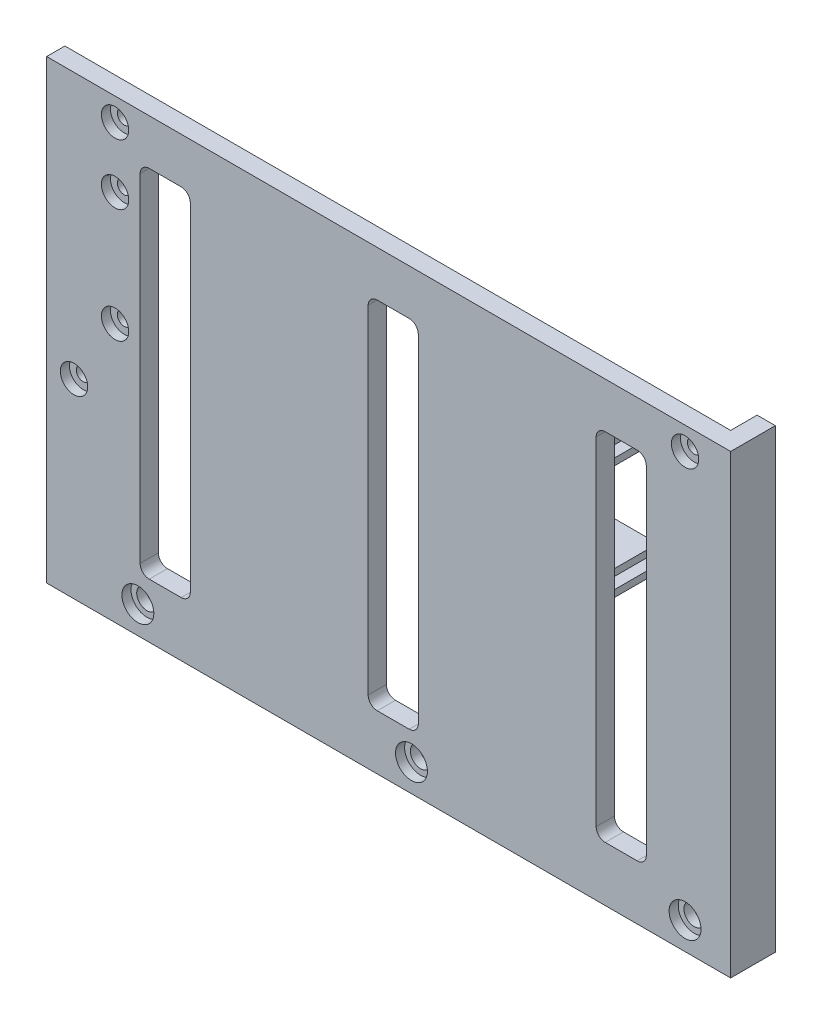
SolidWorks part; units mm, degrees
ref_plane "Front Plane" through (0, 0, 0) normal (0, 0, 1) x (1, 0, 0)
ref_plane "Top Plane" through (0, 0, 0) normal (0, 1, 0) x (1, 0, 0)
ref_plane "Right Plane" through (0, 0, 0) normal (1, 0, 0) x (0, 0, -1)
sketch "Sketch1" plane through (0, 0, 0) normal (0, 1, 0) x (1, 0, 0)
  line L1 (-75, -60) -> (75, -60)
  line L2 (-75, -60) -> (-75, -56)
  line L3 (-75, -56) -> (75, -56)
  line L4 (75, -60) -> (75, -56)
  dimension "D1" = 4
extrude "Boss-Extrude1" add sketch "Sketch1" along normal blind 100 contours L1 L4 L3 L2
sketch "Sketch7" plane through (0, 0, 60) normal (0, 0, 1) x (1, 0, 0)
  line L1 (-7.8417, 2) -> (47.18, 2)
  line L2 (-7.8417, 2) -> (-7.8417, 11.6942)
  line L3 (-7.8417, 11.6942) -> (47.18, 11.6942)
  line L4 (47.18, 2) -> (47.18, 11.6942)
  line L5 (75, 100) -> (75, 0) construction
  line L6 (-75, 0) -> (75, 0) construction
  dimension "D1" = 27.82
  dimension "D2" = 2
extrude "Cut-Extrude1" [suppressed] cut sketch "Sketch7" against normal up to next
sketch "Sketch9" plane through (0, 0, 56) normal (0, 0, -1) x (-1, 0, 0)
  line L0 (75, 0) -> (-75, 0) construction
  line L1 (-71, 100) -> (-75, 100)
  line L2 (-71, 100) -> (-71, 0)
  line L3 (-71, 0) -> (-75, 0)
  line L4 (-75, 100) -> (-75, 0)
  dimension "D1" = 4
extrude "Boss-Extrude4" add sketch "Sketch9" along normal blind 5.8
sketch "Sketch10" plane through (0, 0, 56) normal (0, 0, -1) x (-1, 0, 0)
  line L0 (75, 0) -> (-71, 0) construction
  line L1 (-40, 51.5) -> (-20, 51.5)
  line L2 (-40, 51.5) -> (-40, 50)
  line L3 (-40, 50) -> (-20, 50)
  line L4 (-20, 51.5) -> (-20, 50)
  line L5 (-75, 100) -> (-75, 0) construction
  dimension "D1" = 50
  dimension "D2" = 1.5
  dimension "D3" = 35
  dimension "D4" = 20
extrude "Boss-Extrude5" add sketch "Sketch10" along normal blind 15
pattern_linear "LPattern1" count 2 spacing 60 along (-1, 0, 0) of "Boss-Extrude5"
pattern_linear "LPattern2" count 2 spacing 25 along (0, 1, 0) of "LPattern1", "Boss-Extrude5"
pattern_linear "LPattern3" count 2 spacing 4 along (0, 1, 0) of "LPattern2", "Boss-Extrude5", "LPattern1"
sketch "Sketch12" plane through (118.4209, 9.5564, 60) normal (0, 0, 1) x (1, 0, 0)
  line L2 (-43.4209, 90.4436) -> (-43.4209, -9.5564) construction
  line L3 (-193.4209, -9.5564) -> (-43.4209, -9.5564) construction
  circle A0 centre (-53.4209, -3.5564) radius 3.5
  dimension "D1" = 10
  dimension "D2" = 6
extrude "Cut-Extrude2" cut sketch "Sketch12" against normal blind 2
sketch "Sketch14" plane through (118.4209, 9.5564, 58) normal (0, 0, 1) x (1, 0, 0)
  circle A0 centre (-53.4209, -3.5564) radius 2.25
extrude "Cut-Extrude3" cut sketch "Sketch14" against normal up to next
pattern_linear "LPattern4" count 3 spacing 60 along (-1, 0, 0) of "Cut-Extrude3", "Cut-Extrude2"
sketch "Sketch16" plane through (-5.3809, 91.6326, 60) normal (0, 0, 1) x (1, 0, 0)
  line L0 (-69.6191, 8.3674) -> (80.3809, 8.3674) construction
  line L1 (-69.6191, 8.3674) -> (-69.6191, -91.6326) construction
  circle A0 centre (-54.6191, -9.8826) radius 3
  dimension "D1" = 18.25
  dimension "D2" = 15
extrude "Cut-Extrude4" cut sketch "Sketch16" against normal blind 2
sketch "Sketch18" plane through (-5.3809, 91.6326, 58) normal (0, 0, 1) x (1, 0, 0)
  circle A0 centre (-54.6191, -9.8826) radius 1.5
extrude "Cut-Extrude5" cut sketch "Sketch18" against normal up to next
pattern_linear "LPattern5" count 2 spacing 25 along (0, -1, 0) of "Cut-Extrude5", "Cut-Extrude4"
sketch "Sketch19" plane through (0, 0, 56) normal (0, 0, -1) x (-1, 0, 0)
  line L0 (75, 100) -> (-71, 100) construction
  line L1 (62.5, 90) -> (72.5, 90)
  line L2 (62.5, 90) -> (62.5, 83)
  line L3 (62.5, 83) -> (72.5, 83)
  line L4 (72.5, 90) -> (72.5, 83)
  line L5 (75, 100) -> (75, 0) construction
  dimension "D1" = 10
  dimension "D2" = 10
  dimension "D3" = 7
  dimension "D4" = 2.5
extrude "Cut-Extrude6" cut sketch "Sketch19" against normal blind 3
pattern_linear "LPattern6" count 2 spacing 55 along (0, -1, 0) of "Cut-Extrude6"
sketch "Sketch20" plane through (0, 0, 56) normal (0, 0, -1) x (-1, 0, 0)
  line L0 (75, 100) -> (75, 0) construction
  line L1 (43.5, 90) -> (54.5, 90)
  line L2 (43.5, 90) -> (43.5, 12)
  line L3 (43.5, 12) -> (54.5, 12)
  line L4 (54.5, 90) -> (54.5, 12)
  line L5 (75, 100) -> (-71, 100) construction
  line L6 (75, 0) -> (-71, 0) construction
  dimension "D1" = 11
  dimension "D2" = 20.5
  dimension "D3" = 10
  dimension "D4" = 12
extrude "Cut-Extrude7" cut sketch "Sketch20" against normal up to next
fillet "Fillet4" radius 2 4 edges at (-54.5, 12, 58) (-43.5, 12, 58) (-54.5, 90, 58) (-43.5, 90, 58)
pattern_linear "LPattern7" count 3 spacing 50 along (1, 0, 0) of "Cut-Extrude7", "Fillet4"
sketch "Sketch21" plane through (0, 0, 56) normal (0, 0, -1) x (-1, 0, 0)
  line L0 (75, 100) -> (75, 0) construction
  line L1 (25, 93.5387) -> (33, 93.5387)
  line L2 (25, 93.5387) -> (25, 83.5387)
  line L3 (25, 83.5387) -> (33, 83.5387)
  line L4 (33, 93.5387) -> (33, 83.5387)
  dimension "D1" = 8
  dimension "D2" = 42
  dimension "D3" = 10
extrude "Cut-Extrude8" cut sketch "Sketch21" against normal blind 3
pattern_linear "LPattern8" count 2 spacing 60 along (1, 0, 0) of "Cut-Extrude8"
sketch "Sketch23" plane through (-14.0948, 47.7647, 60) normal (0, 0, 1) x (1, 0, 0)
  line L2 (-60.9052, 52.2353) -> (-60.9052, -47.7647) construction
  circle A0 centre (-54.9052, -6.0147) radius 3
  circle A1 centre (-45.9052, 8.9853) radius 1.5 construction
  point P4 (0, 0)
  point P5 (0, 0)
  point P6 (-60.9052, -1.4478)
  dimension "D1" = 15
  dimension "D2" = 6
extrude "Cut-Extrude9" cut sketch "Sketch23" against normal blind 2
sketch "Sketch25" plane through (-14.0948, 47.7647, 58) normal (0, 0, 1) x (1, 0, 0)
  circle A0 centre (-54.9052, -6.0147) radius 1.5
extrude "Cut-Extrude10" cut sketch "Sketch25" against normal up to next
sketch "Sketch27" plane through (-5.4341, 100.0268, 60) normal (0, 0, 1) x (1, 0, 0)
  circle A0 centre (-54.5659, -5.0268) radius 3
  circle A2 centre (-54.5659, -18.2768) radius 1.5 construction
  point P2 (0, 0)
  point P4 (0, 0)
  point P5 (0, 0)
  point P6 (-60.9052, -1.4478)
  point P10 (-54.5659, -18.2768)
  dimension "D1" = 1.5
  dimension "D2" = 0
extrude "Cut-Extrude11" cut sketch "Sketch27" against normal blind 2
sketch "Sketch29" plane through (-5.4341, 100.0268, 58) normal (0, 0, 1) x (1, 0, 0)
  circle A0 centre (-54.5659, -5.0268) radius 1.5
extrude "Cut-Extrude12" cut sketch "Sketch29" against normal up to next
pattern_linear "LPattern10" count 2 spacing 125 along (1, 0, 0) of "Cut-Extrude12", "Cut-Extrude11"
